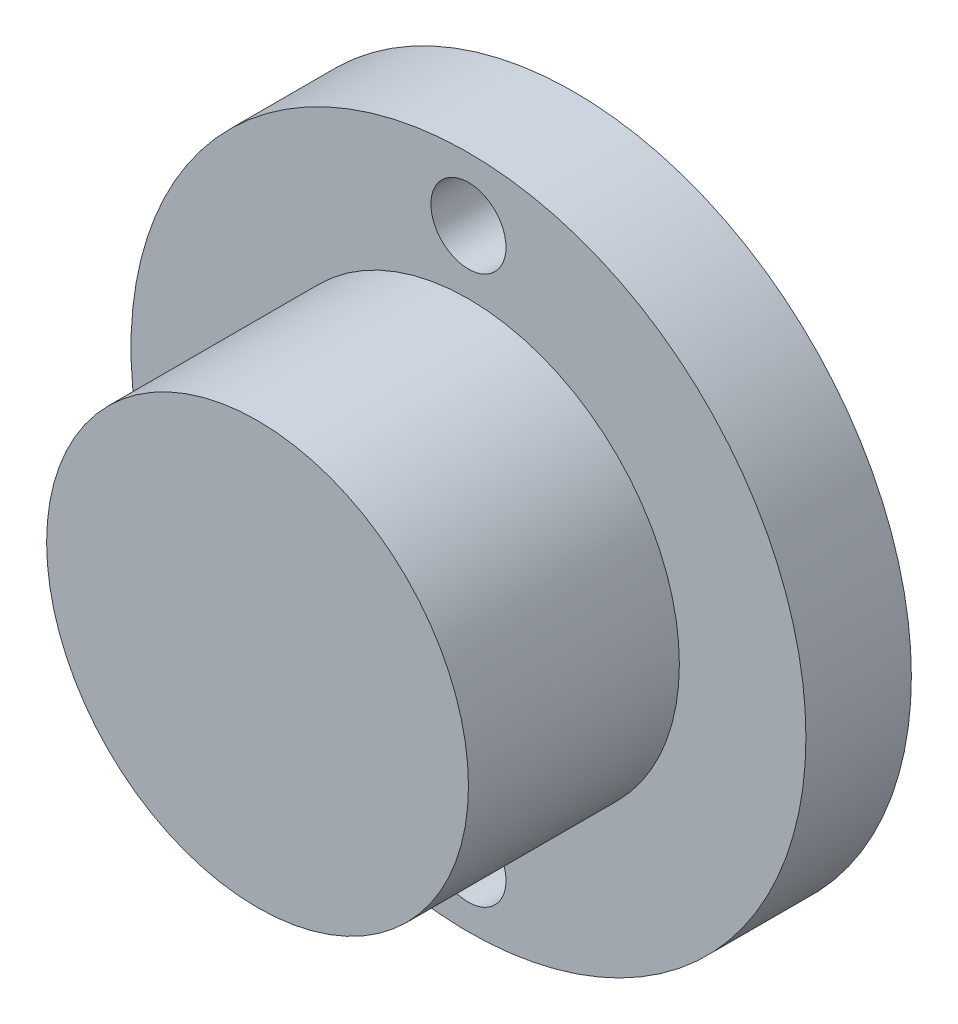
SolidWorks part; units mm, degrees
ref_plane "Front Plane" through (0, 0, 0) normal (0, 0, 1) x (1, 0, 0)
ref_plane "Top Plane" through (0, 0, 0) normal (0, 1, 0) x (1, 0, 0)
ref_plane "Right Plane" through (0, 0, 0) normal (1, 0, 0) x (0, 0, -1)
sketch "Sketch1" plane through (0, 0, 0) normal (0, 0, 1) x (1, 0, 0)
  circle A0 centre (0, 0) radius 10.16
  dimension "D1" = 20.32
extrude "Boss-Extrude2" add sketch "Sketch1" along normal blind 3.175
sketch "Sketch4" plane through (0, 0, 3.175) normal (0, 0, 1) x (1, 0, 0)
  circle A0 centre (0, 0) radius 6.35
  dimension "D1" = 12.7
extrude "Boss-Extrude3" add sketch "Sketch4" along normal blind 6.35
sketch "Sketch5" plane through (0, 0, 0) normal (0, 0, -1) x (-1, 0, 0)
  circle A0 centre (0, 0) radius 4.7625
  dimension "D1" = 9.525
extrude "Cut-Extrude3" cut sketch "Sketch5" against normal blind 6.35
sketch "Sketch6" plane through (0, 0, 3.175) normal (0, 0, 1) x (1, 0, 0)
  circle A0 centre (0, 8.255) radius 1.1303
  circle A1 centre (0, 0) radius 8.255 construction
  circle A2 centre (0, -8.255) radius 1.1303
  point P5 (0, 0)
  point P6 (0, 0)
  dimension "D1" = 2.2606
  dimension "D2" = 16.51
  dimension "D3" = 2.2606
extrude "Cut-Extrude4" cut sketch "Sketch6" against normal through all
